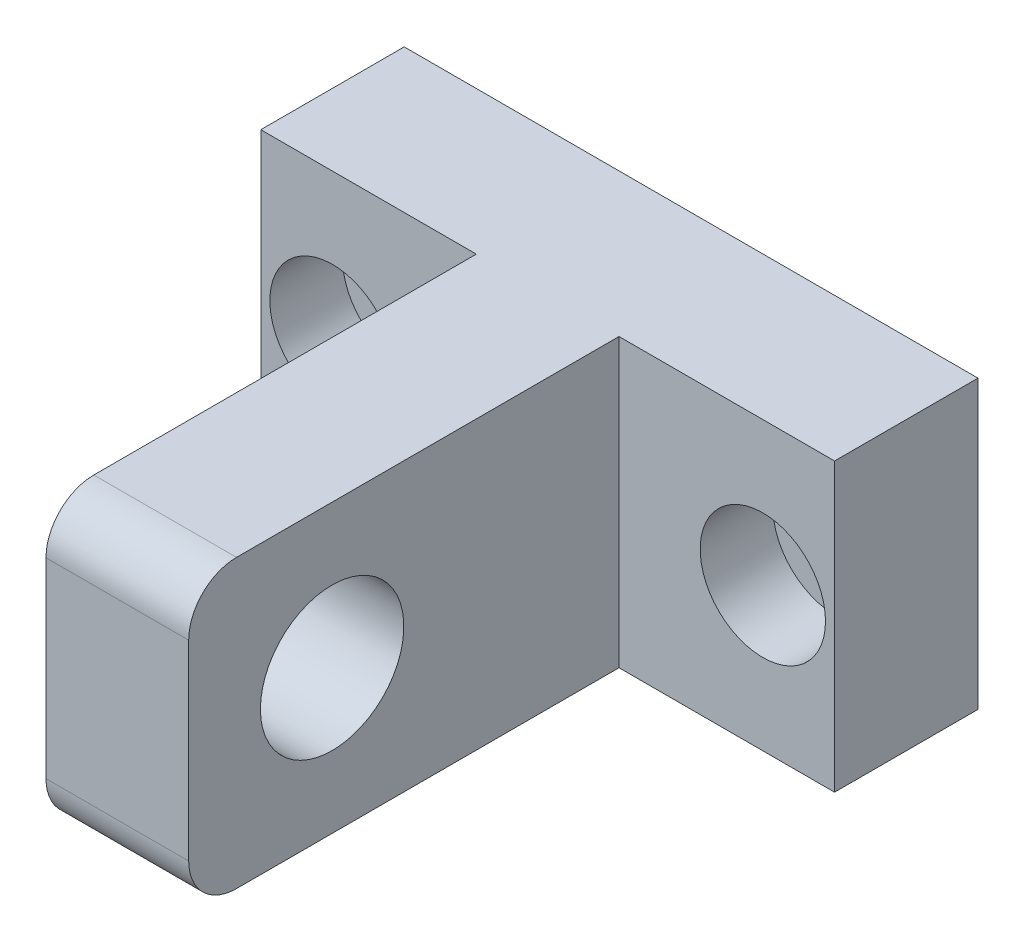
SolidWorks part; units mm, degrees
ref_plane "Front Plane" through (0, 0, 0) normal (0, 0, 1) x (1, 0, 0)
ref_plane "Top Plane" through (0, 0, 0) normal (0, 1, 0) x (1, 0, 0)
ref_plane "Right Plane" through (0, 0, 0) normal (1, 0, 0) x (0, 0, -1)
sketch "Sketch1" plane through (0, 0, 0) normal (0, 0, 1) x (1, 0, 0)
  line L0 (-19.05, -9.525) -> (19.05, 9.525) construction
  line L1 (-19.05, 9.525) -> (19.05, 9.525)
  line L2 (-19.05, 9.525) -> (-19.05, -9.525)
  line L3 (-19.05, -9.525) -> (19.05, -9.525)
  line L4 (19.05, 9.525) -> (19.05, -9.525)
  line L5 (-14.2875, 0) -> (14.2875, 0) construction
  line L6 (-4.7371, 9.525) -> (-4.7371, -9.525) construction
  line L7 (4.7371, 9.525) -> (4.7371, -9.525) construction
  line L8 (-4.7371, 9.525) -> (4.7371, -9.525) construction
  circle A0 centre (-14.2875, 0) radius 2.5337
  circle A1 centre (14.2875, 0) radius 2.5337
  dimension "D4" = 5.0673
  dimension "D1" = 38.1
  dimension "D2" = 19.05
  dimension "D3" = 28.575
  dimension "D5" = 9.4742
extrude "Boss-Extrude1" add sketch "Sketch1" along normal blind 9.525
sketch "Sketch2" plane through (0, 0, 9.525) normal (0, 0, 1) x (1, 0, 0)
  circle A0 centre (-14.2875, 0) radius 4.1605
  circle A1 centre (14.2875, 0) radius 4.1605
  dimension "D1" = 8.321
extrude "Cut-Extrude1" cut sketch "Sketch2" against normal blind 4.826
sketch "Sketch3" plane through (0, 0, 0) normal (1, 0, 0) x (0, 0, -1)
  line L0 (-9.525, -9.525) -> (-9.525, 9.525) construction
  line L2 (-38.1, 9.525) -> (-9.525, 9.525)
  line L3 (-38.1, 9.525) -> (-38.1, -9.525)
  line L4 (-38.1, -9.525) -> (-9.525, -9.525)
  line L5 (-9.525, 9.525) -> (-9.525, -9.525)
  circle A0 centre (-28.575, 0) radius 4.7625
  dimension "D2" = 9.525
  dimension "D1" = 19.05
  dimension "D3" = 9.525
extrude "Boss-Extrude2" add sketch "Sketch3" along normal up to vertex (4.7371 mm away) and the other way up to vertex (4.7371 mm away) up to point (4.7371, 9.525, 0) other way up to point (-4.7371, 9.525, 0)
fillet "Fillet1" radius 3.175 2 edges at (0, -9.525, 38.1) (0, 9.525, 38.1)
